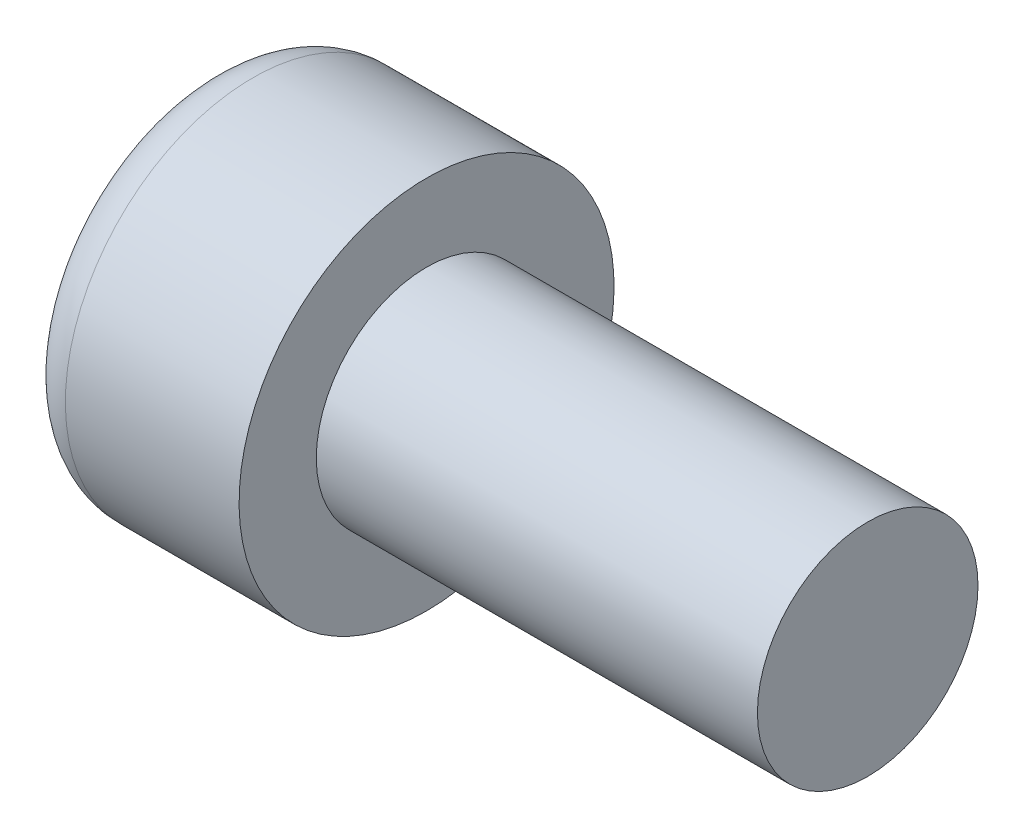
SolidWorks part; units mm, degrees
material "Plain Carbon Steel"
ref_plane "Front Plane" through (0, 0, 0) normal (0, 0, 1) x (1, 0, 0)
ref_plane "Top Plane" through (0, 0, 0) normal (0, 1, 0) x (1, 0, 0)
ref_plane "Right Plane" through (0, 0, 0) normal (1, 0, 0) x (0, 0, -1)
sketch "Sketch1" plane through (0, 0, 0) normal (0, 0, 1) x (1, 0, 0)
  line L0 (0, 0) -> (0, 3.1875)
  line L1 (1.0625, 4.25) -> (5, 4.25)
  line L2 (5, 4.25) -> (5, 2.5)
  line L3 (5, 2.5) -> (15, 2.5)
  line L4 (15, 2.5) -> (15, 0)
  line L5 (15, 0) -> (0, 0) construction
  line L6 (1.0625, 3.1875) -> (1.0625, 2.125) construction
  line L7 (1.0625, 2.125) -> (1.0625, 1.0625) construction
  line L8 (1.0625, 1.0625) -> (1.0625, 0) construction
  line L9 (1.0625, 4.25) -> (1.0625, 3.1875) construction
  line L10 (0, 0) -> (15, 0)
  arc A0 (0, 3.1875) -> (1.0625, 4.25) centre (1.0625, 3.1875) cw
  dimension "D1" = 5
  dimension "D2" = 8.5
  dimension "D3" = 5
  dimension "D4" = 10
revolve "Revolve1" add sketch "Sketch1" angle 360 about L10
sketch "Sketch2" plane through (0, 0, 0) normal (-1, 0, 0) x (0, 0, 1)
  line L1 (0, 2.3094) -> (-2, 1.1547)
  line L2 (-2, 1.1547) -> (-2, -1.1547)
  line L3 (-2, -1.1547) -> (0, -2.3094)
  line L4 (0, -2.3094) -> (2, -1.1547)
  line L5 (2, -1.1547) -> (2, 1.1547)
  line L6 (2, 1.1547) -> (0, 2.3094)
  circle A0 centre (0, 0) radius 2 construction
  dimension "D1" = 4
extrude "Cut-Extrude1" cut sketch "Sketch2" against normal blind 2.5
